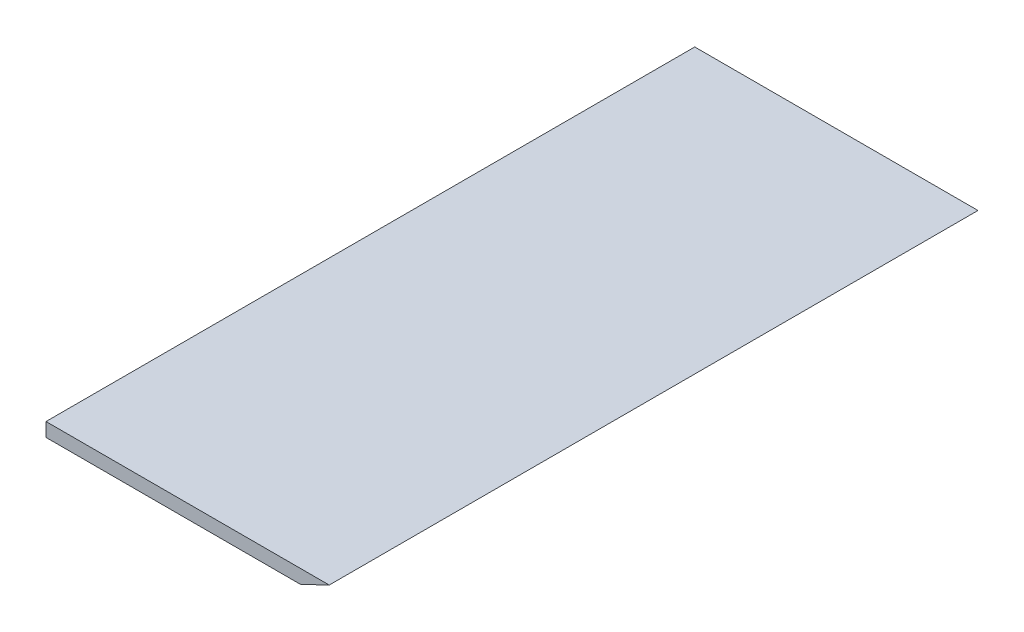
SolidWorks part; units mm, degrees
ref_plane "Front Plane" through (0, 0, 0) normal (0, 0, 1) x (1, 0, 0)
ref_plane "Top Plane" through (0, 0, 0) normal (0, 1, 0) x (1, 0, 0)
ref_plane "Right Plane" through (0, 0, 0) normal (1, 0, 0) x (0, 0, -1)
sketch "Sketch1" plane through (0, 0, 0) normal (0, 0, 1) x (1, 0, 0)
  line L0 (0, 0) -> (117.094, 0)
  line L1 (0, 0) -> (0, 6.35)
  line L2 (0, 6.35) -> (130.302, 6.35)
  line L3 (130.302, 6.35) -> (117.094, 0)
extrude "Boss-Extrude2" add sketch "Sketch1" along normal blind 298.45
